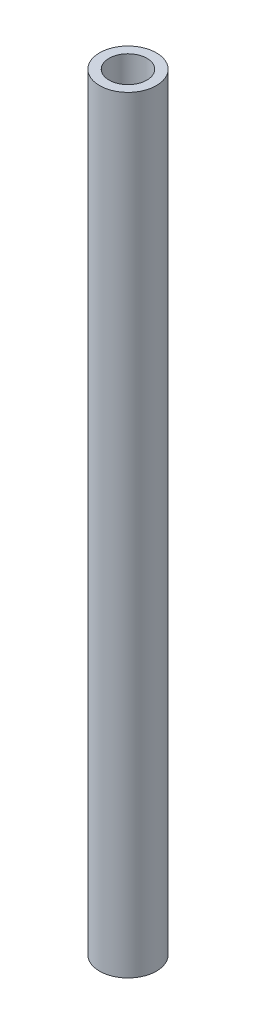
SolidWorks part; units mm, degrees
other "Frame Spacer Tube Left"
ref_plane "Front Plane" through (0, 0, 0) normal (0, 0, 1) x (1, 0, 0)
ref_plane "Top Plane" through (0, 0, 0) normal (0, 1, 0) x (1, 0, 0)
ref_plane "Right Plane" through (0, 0, 0) normal (1, 0, 0) x (0, 0, -1)
sketch3d "Base Outline Sketch datum points"
  point P0 (0, 69.6, 0)
  point P1 (10, 69.6, 0)
  point P2 (0, 69.6, -10)
ref_plane "Base Outline Sketch plane" through (0, 69.6, 0) normal (0, 1, 0) x (1, 0, 0)
sketch "Base Outline Sketch" plane through (0, 69.6, 0) normal (0, 1, 0) x (1, 0, 0)
  circle A0 centre (-56.2917, -50) radius 3
  circle A1 centre (-56.2917, -50) radius 2
extrude "Base Outline" add sketch "Base Outline Sketch" along normal blind 81 separate body
